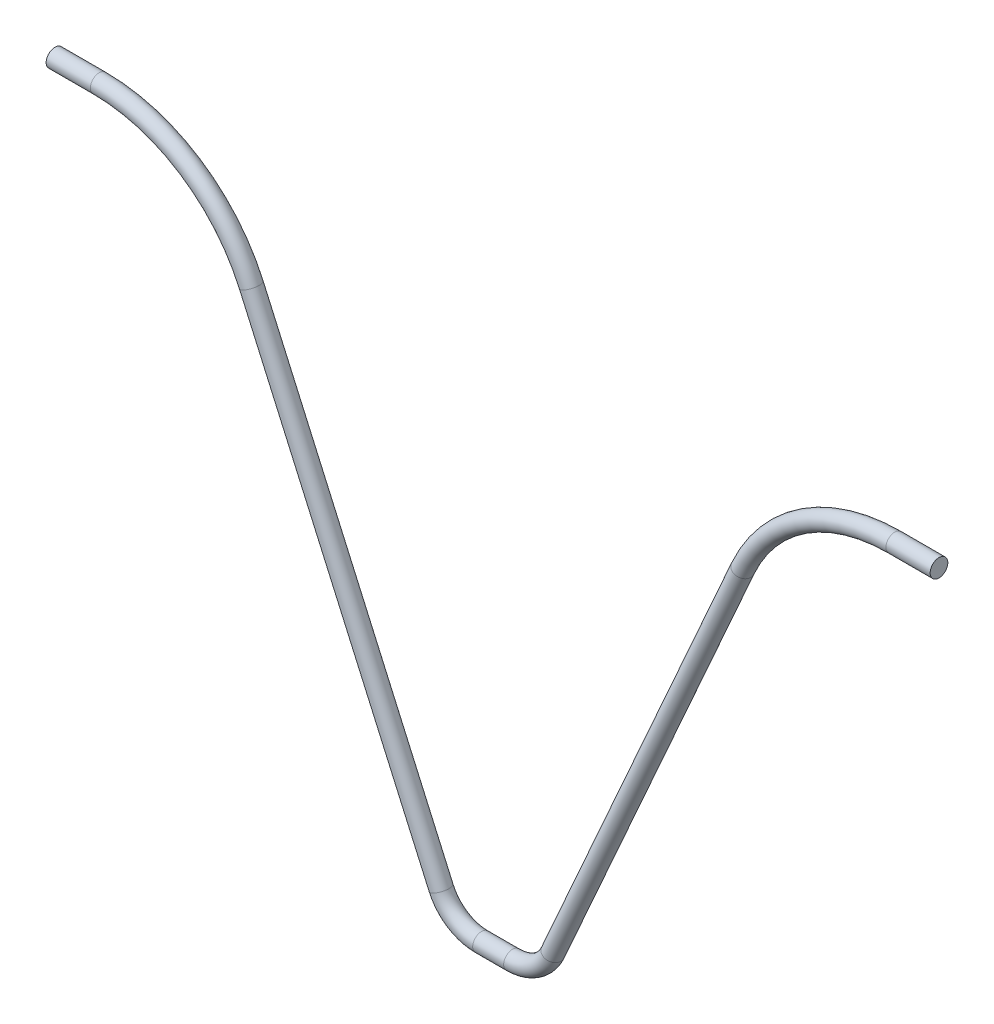
SolidWorks part; units mm, degrees
ref_plane "Front Plane" through (0, 0, 0) normal (0, 0, 1) x (1, 0, 0)
ref_plane "Top Plane" through (0, 0, 0) normal (0, 1, 0) x (1, 0, 0)
ref_plane "Right Plane" through (0, 0, 0) normal (1, 0, 0) x (0, 0, -1)
sketch "Sketch1" plane through (0, 0, 0) normal (0, 0, 1) x (1, 0, 0)
  line L0 (0, -410) -> (0, 542) construction
  line L1 (-35, -410) -> (35, -410)
  line L2 (126.3884, -350.5975) -> (555.9416, 616.362)
  line L3 (900, 840) -> (1000, 840)
  line L4 (-900, 840) -> (-1000, 840)
  line L5 (-126.3884, -350.5975) -> (-555.9416, 616.362)
  arc A0 (555.9416, 616.362) -> (900, 840) centre (900, 463.5207) cw
  arc A1 (-555.9416, 616.362) -> (-900, 840) centre (-900, 463.5207) ccw
  arc A2 (35, -410) -> (126.3884, -350.5975) centre (35, -310) ccw
  arc A3 (-126.3884, -350.5975) -> (-35, -410) centre (-35, -310) ccw
  point P15 (100, -410)
  point P18 (-100, -410)
  dimension "D5" = 100
  dimension "D1" = 100
  dimension "D2" = 100
  dimension "D3" = 1000
  dimension "D4" = 1250
  dimension "D6" = 70
ref_plane "Plane1" through (-1000, 0, 0) normal (1, 0, 0) x (0, 0, -1)
sketch "Sketch3" plane through (-1000, 0, 0) normal (1, 0, 0) x (0, 0, -1)
  circle A0 centre (0, 840) radius 20
  point P3 (0, 0)
  point P10 (0, 0)
  dimension "D1" = 40
sweep "Sweep1" add profiles "Sketch3" path "Sketch1"
